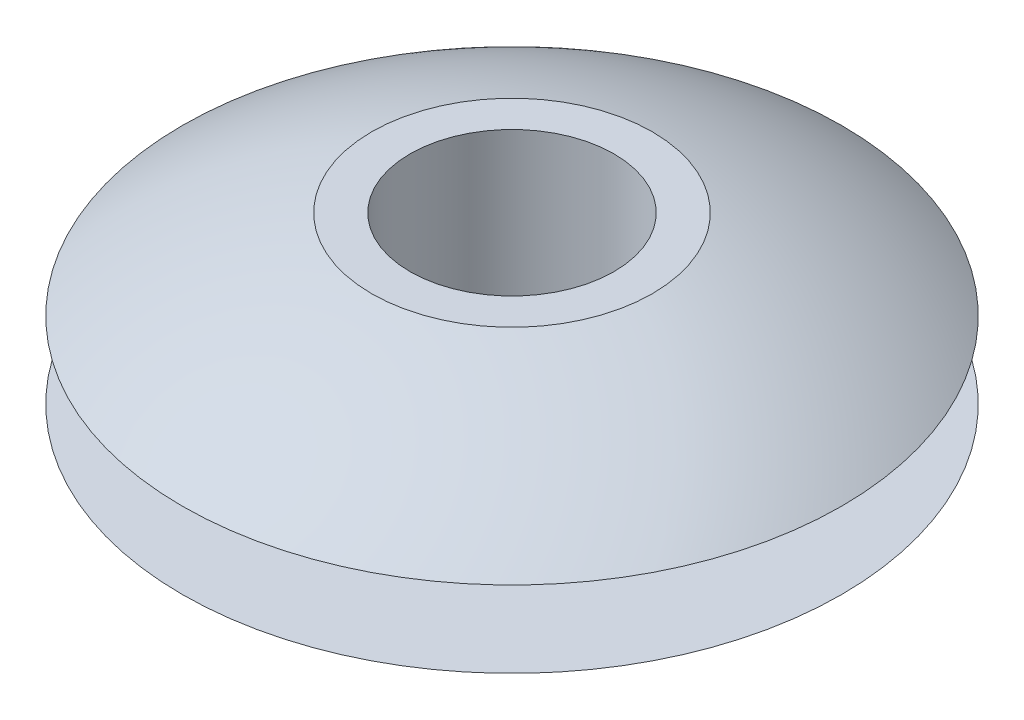
SolidWorks part; units mm, degrees
ref_plane "前视基准面" through (0, 0, 0) normal (0, 0, 1) x (1, 0, 0)
ref_plane "上视基准面" through (0, 0, 0) normal (0, 1, 0) x (1, 0, 0)
ref_plane "右视基准面" through (0, 0, 0) normal (1, 0, 0) x (0, 0, -1)
sketch "草图2" plane through (0, 0, 0) normal (1, 0, 0) x (0, 0, -1)
  line L0 (-56.193, 0) -> (49.8253, 0) construction
  line L1 (0, 32.3386) -> (0, -25.9352) construction
  line L2 (6.4635, 0.75) -> (2.75, 0.75)
  line L3 (2.75, 0.75) -> (2.75, -0.75)
  line L4 (2.75, 2.5) -> (2, 2.5)
  line L5 (2.75, -2.5) -> (2, -2.5)
  line L6 (6.4635, -0.75) -> (2.75, -0.75)
  line L7 (2, 2.5) -> (2, -2.5)
  arc A0 (2.75, 2.5) -> (6.4635, 0.75) centre (0, -8.1507) cw
  arc A1 (2.75, -2.5) -> (6.4635, -0.75) centre (0, 8.1507) ccw
  point P16 (2.75, 0)
  dimension "D1" = 11
  dimension "D2" = 0.75
  dimension "D3" = 2.5
  dimension "D4" = 2.75
  dimension "D5" = 2
revolve "旋转1" add sketch "草图2" angle 360 about L1
